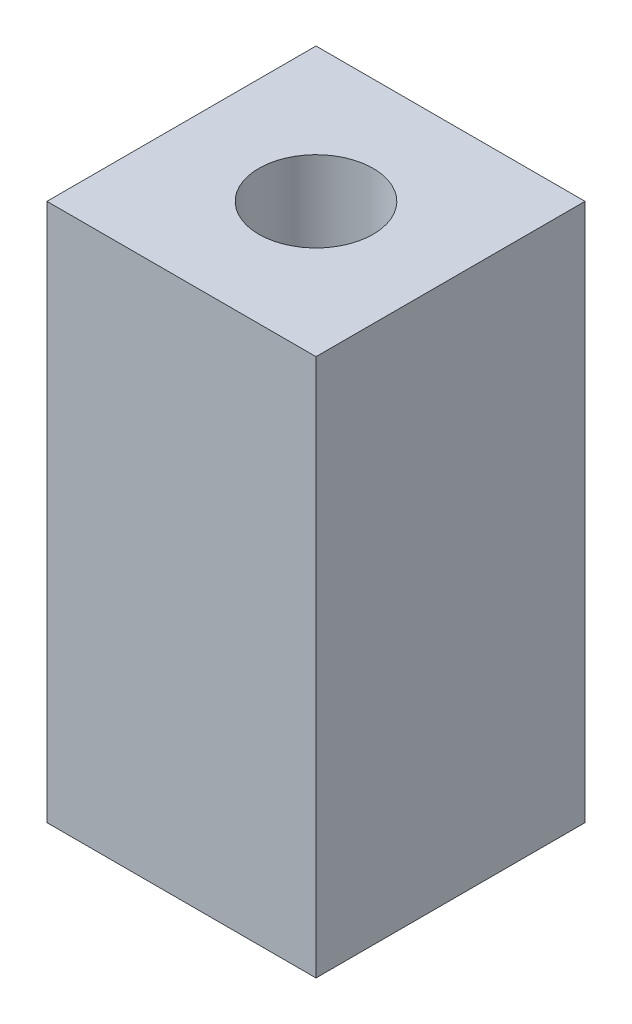
SolidWorks part; units mm, degrees
ref_plane "Front Plane" through (0, 0, 0) normal (0, 0, 1) x (1, 0, 0)
ref_plane "Top Plane" through (0, 0, 0) normal (0, 1, 0) x (1, 0, 0)
ref_plane "Right Plane" through (0, 0, 0) normal (1, 0, 0) x (0, 0, -1)
sketch "Sketch1" plane through (0, 0, 0) normal (0, 1, 0) x (1, 0, 0)
  line L1 (-7.9375, -7.9375) -> (7.9375, -7.9375)
  line L2 (-7.9375, -7.9375) -> (-7.9375, 7.9375)
  line L3 (-7.9375, 7.9375) -> (7.9375, 7.9375)
  line L4 (7.9375, -7.9375) -> (7.9375, 7.9375)
  line L5 (-7.9375, -7.9375) -> (7.9375, 7.9375) construction
  line L6 (-7.9375, 7.9375) -> (7.9375, -7.9375) construction
  circle A0 centre (0, 0) radius 3.3734
  point P0 (0, 0)
  dimension "D3" = 6.7469
  dimension "D1" = 15.875
  dimension "D2" = 15.875
extrude "Boss-Extrude1" add sketch "Sketch1" along normal blind 31.75
